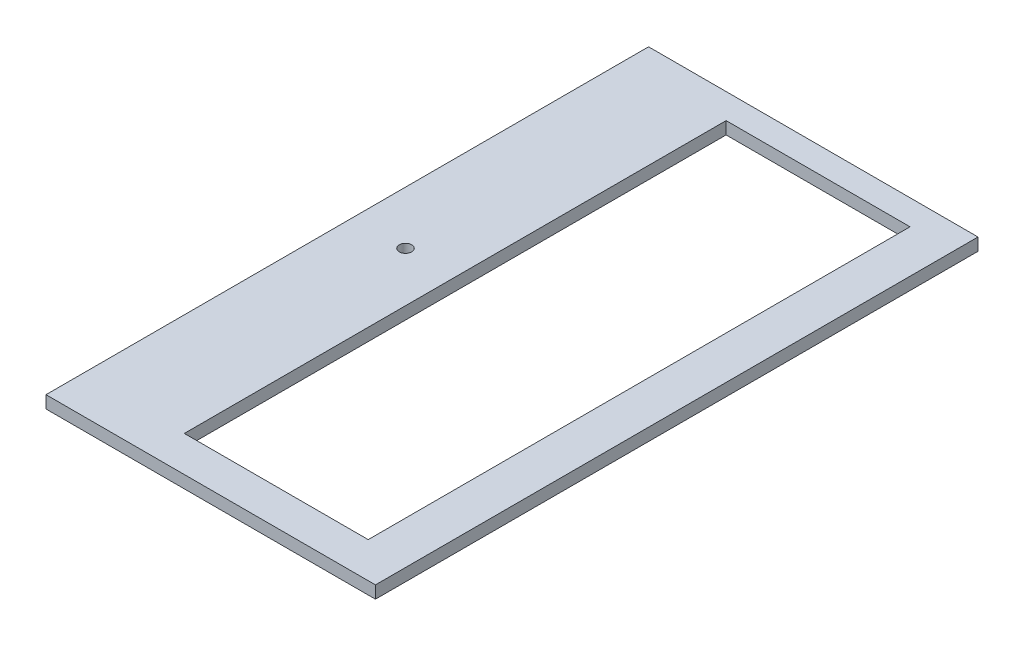
SolidWorks part; units mm, degrees
ref_plane "Front Plane" through (0, 0, 0) normal (0, 0, 1) x (1, 0, 0)
ref_plane "Top Plane" through (0, 0, 0) normal (0, 1, 0) x (1, 0, 0)
ref_plane "Right Plane" through (0, 0, 0) normal (1, 0, 0) x (0, 0, -1)
sketch "Sketch1" plane through (0, 0, 0) normal (0, 1, 0) x (1, 0, 0)
  line L0 (0, -112.5) -> (0, 0) construction
  line L1 (-80, 112.5) -> (100, 112.5)
  line L3 (-80, -112.5) -> (100, -112.5)
  line L4 (100, 112.5) -> (100, -112.5)
  line L5 (0, 0) -> (0, 112.5) construction
  arc A0 (-80, 112.5) -> (-80, -112.5) centre (-80, 0) ccw
  dimension "D1" = 100
  dimension "D4" = 112.5
  dimension "D2" = 80
  dimension "D3" = 225
extrude "Boss-Extrude1" add sketch "Sketch1" against normal blind 3.175
sketch "Sketch2" plane through (0, 0, 0) normal (0, 1, 0) x (1, 0, 0)
  line L0 (36.144, -74.2188) -> (36.144, -67.8688) construction
  line L1 (52.019, 0) -> (52.019, -89.9668) construction
  line L2 (11.887, -89.9668) -> (92.151, -89.9668)
  line L3 (11.887, -89.9668) -> (11.887, -102.9208)
  line L4 (11.887, -102.9208) -> (92.151, -102.9208)
  line L5 (92.151, -89.9668) -> (92.151, -102.9208)
  line L6 (11.887, 89.9668) -> (92.151, 89.9668)
  line L7 (11.887, 89.9668) -> (11.887, 102.9208)
  line L8 (11.887, 102.9208) -> (92.151, 102.9208)
  line L9 (92.151, 89.9668) -> (92.151, 102.9208)
  line L10 (52.019, 0) -> (52.019, 89.9668) construction
  line L11 (36.144, -67.8688) -> (36.144, -61.5188) construction
  line L12 (36.144, -61.5188) -> (36.144, -55.1688) construction
  line L13 (36.144, -55.1688) -> (36.144, -48.8188) construction
  line L14 (36.144, -48.8188) -> (36.144, -42.4688) construction
  line L15 (36.144, -42.4688) -> (36.144, -36.1188) construction
  line L16 (67.894, -74.2188) -> (67.894, -67.8688) construction
  line L17 (67.894, -67.8688) -> (67.894, -61.5188) construction
  line L18 (67.894, -61.5188) -> (67.894, -55.1688) construction
  line L19 (67.894, -55.1688) -> (67.894, -48.8188) construction
  line L20 (67.894, -48.8188) -> (67.894, -42.4688) construction
  line L21 (67.894, -42.4688) -> (67.894, -36.1188) construction
  line L22 (36.144, -74.2188) -> (67.894, -74.2188) construction
  line L23 (36.144, -36.1188) -> (67.894, -36.1188) construction
  line L24 (36.144, 36.1188) -> (36.144, 42.4688) construction
  line L25 (36.144, 42.4688) -> (36.144, 48.8188) construction
  line L26 (36.144, 48.8188) -> (36.144, 55.1688) construction
  line L27 (36.144, 55.1688) -> (36.144, 61.5188) construction
  line L28 (36.144, 61.5188) -> (36.144, 67.8688) construction
  line L29 (36.144, 67.8688) -> (36.144, 74.2188) construction
  line L30 (67.894, 36.1188) -> (67.894, 42.4688) construction
  line L31 (67.894, 42.4688) -> (67.894, 48.8188) construction
  line L32 (67.894, 48.8188) -> (67.894, 55.1688) construction
  line L33 (67.894, 55.1688) -> (67.894, 61.5188) construction
  line L34 (67.894, 61.5188) -> (67.894, 67.8688) construction
  line L35 (67.894, 67.8688) -> (67.894, 74.2188) construction
  line L36 (36.144, 74.2188) -> (67.894, 74.2188) construction
  line L37 (36.144, 36.1188) -> (67.894, 36.1188) construction
  line L38 (36.144, 55.1688) -> (52.019, 55.1688) construction
  line L39 (52.019, 55.1688) -> (67.894, 55.1688) construction
  line L40 (0, -112.5) -> (0, 112.5) construction
  line L41 (0, 0) -> (52.019, 0) construction
  line L42 (100, 112.5) -> (-80, 112.5) construction
  line L43 (-80, -112.5) -> (100, -112.5) construction
  circle A1 centre (36.144, -74.2188) radius 1.5875
  circle A2 centre (36.144, -67.8688) radius 1.5875
  circle A3 centre (36.144, -61.5188) radius 1.5875
  circle A4 centre (36.144, -55.1688) radius 1.5875
  circle A5 centre (36.144, -48.8188) radius 1.5875
  circle A6 centre (36.144, -42.4688) radius 1.5875
  circle A7 centre (36.144, -36.1188) radius 1.5875
  circle A8 centre (67.894, -74.2188) radius 1.5875
  circle A9 centre (67.894, -67.8688) radius 1.5875
  circle A10 centre (67.894, -61.5188) radius 1.5875
  circle A11 centre (67.894, -55.1688) radius 1.5875
  circle A12 centre (67.894, -48.8188) radius 1.5875
  circle A13 centre (67.894, -42.4688) radius 1.5875
  circle A14 centre (67.894, -36.1188) radius 1.5875
  circle A15 centre (36.144, 74.2188) radius 1.5875
  circle A16 centre (36.144, 67.8688) radius 1.5875
  circle A17 centre (36.144, 61.5188) radius 1.5875
  circle A18 centre (36.144, 55.1688) radius 1.5875
  circle A19 centre (36.144, 48.8188) radius 1.5875
  circle A20 centre (36.144, 42.4688) radius 1.5875
  circle A21 centre (36.144, 36.1188) radius 1.5875
  circle A22 centre (67.894, 74.2188) radius 1.5875
  circle A23 centre (67.894, 67.8688) radius 1.5875
  circle A24 centre (67.894, 61.5188) radius 1.5875
  circle A25 centre (67.894, 55.1688) radius 1.5875
  circle A26 centre (67.894, 48.8188) radius 1.5875
  circle A27 centre (67.894, 42.4688) radius 1.5875
  circle A28 centre (67.894, 36.1188) radius 1.5875
  dimension "D6" = 3.175
  dimension "D7" = 6.35
  dimension "D8" = 15.875
  dimension "D10" = 3.175
  dimension "D1" = 12.954
  dimension "D2" = 80.264
  dimension "D3" = 179.9336
  dimension "D4" = 15.748
  dimension "D5" = 15.875
  dimension "D9" = 15.875
  dimension "D11" = 6.35
  dimension "D12" = 15.748
  dimension "D13" = 72.2376
  dimension "D14" = 205.8416
  dimension "D15" = 92.151
extrude "Cut-Extrude1" cut sketch "Sketch2" against normal through all
sketch "Sketch7" plane through (0, 0, 0) normal (0, 1, 0) x (1, 0, 0)
  line L0 (10, 112.5) -> (9.5239, 69.215) construction
  line L1 (-37.4661, 69.215) -> (9.5239, 69.215)
  line L2 (-37.4661, 69.215) -> (-37.4661, -69.215)
  line L3 (-37.4661, -69.215) -> (9.5239, -69.215)
  line L4 (9.5239, 69.215) -> (9.5239, -69.215)
  line L5 (100, 112.5) -> (-80, 112.5) construction
  line L6 (9.5239, -69.215) -> (10, -112.5) construction
  line L7 (-80, -112.5) -> (100, -112.5) construction
  circle A0 centre (-50.1661, 0) radius 1.5875
  circle A1 centre (25.5828, 0) radius 1.5875
  circle A2 centre (87.4621, 0) radius 1.5875
  dimension "D3" = 3.175
  dimension "D1" = 46.99
  dimension "D2" = 138.43
  dimension "D4" = 12.7
extrude "Cut-Extrude4" cut sketch "Sketch7" against normal through all
sketch "Sketch8" plane through (0, 0, 0) normal (0, 1, 0) x (1, 0, 0)
  line L0 (-80, 112.5) -> (-80, -112.5) construction
  line L1 (-192.5, 0) -> (100, 0) construction
  line L2 (100, -112.5) -> (100, 112.5) construction
  line L3 (-167.0966, 25.4) -> (-229.7767, 25.4)
  line L4 (-229.7767, 25.4) -> (-229.7767, -25.4)
  line L5 (-229.7767, -25.4) -> (-167.0966, -25.4)
  arc A0 (-80, 112.5) -> (-80, -112.5) centre (-80, 0) ccw construction
  arc A2 (-167.0966, 25.4) -> (-167.0966, -25.4) centre (-167.0966, 0) cw
  point P12 (-80, 0)
  dimension "D2" = 87.0966
  dimension "D1" = 25.4
extrude "Cut-Extrude5" cut sketch "Sketch8" against normal through all
sketch "Sketch9" plane through (0, 0, 0) normal (0, 1, 0) x (1, 0, 0)
  line L0 (0, 120.9245) -> (0, 78.8406)
  line L1 (0, 78.8406) -> (20.4591, 78.8406)
  line L2 (20.4591, 78.8406) -> (20.4591, -78.8406)
  line L3 (20.4591, -78.8406) -> (0, -78.8406)
  line L4 (0, -78.8406) -> (0, -122.5226)
  line L5 (0, -122.5226) -> (114.7482, -122.5226)
  line L6 (114.7482, -122.5226) -> (114.7482, 120.9245)
  line L7 (114.7482, 120.9245) -> (0, 120.9245)
extrude "Cut-Extrude6" cut sketch "Sketch9" against normal through all
sketch "Sketch10" plane through (0, 0, 0) normal (0, 1, 0) x (1, 0, 0)
  line L0 (24.7207, 75.6444) -> (-63.7087, 75.6444)
  line L1 (-63.7087, 75.6444) -> (-63.7087, -78.3079)
  line L2 (24.7207, -86.8312) -> (24.7207, -123.0553)
  line L3 (24.7207, -123.0553) -> (-234.1749, -128.3824)
  line L4 (-234.1749, -128.3824) -> (-239.2835, 119.8965)
  line L5 (-239.2835, 119.8965) -> (24.7207, 119.8965)
  line L6 (24.7207, 119.8965) -> (24.7207, 75.6444)
  line L7 (-63.7087, -78.3079) -> (24.7207, -78.3079)
  line L8 (24.7207, -78.3079) -> (24.7207, -86.8312)
extrude "Cut-Extrude7" cut sketch "Sketch10" against normal through all
